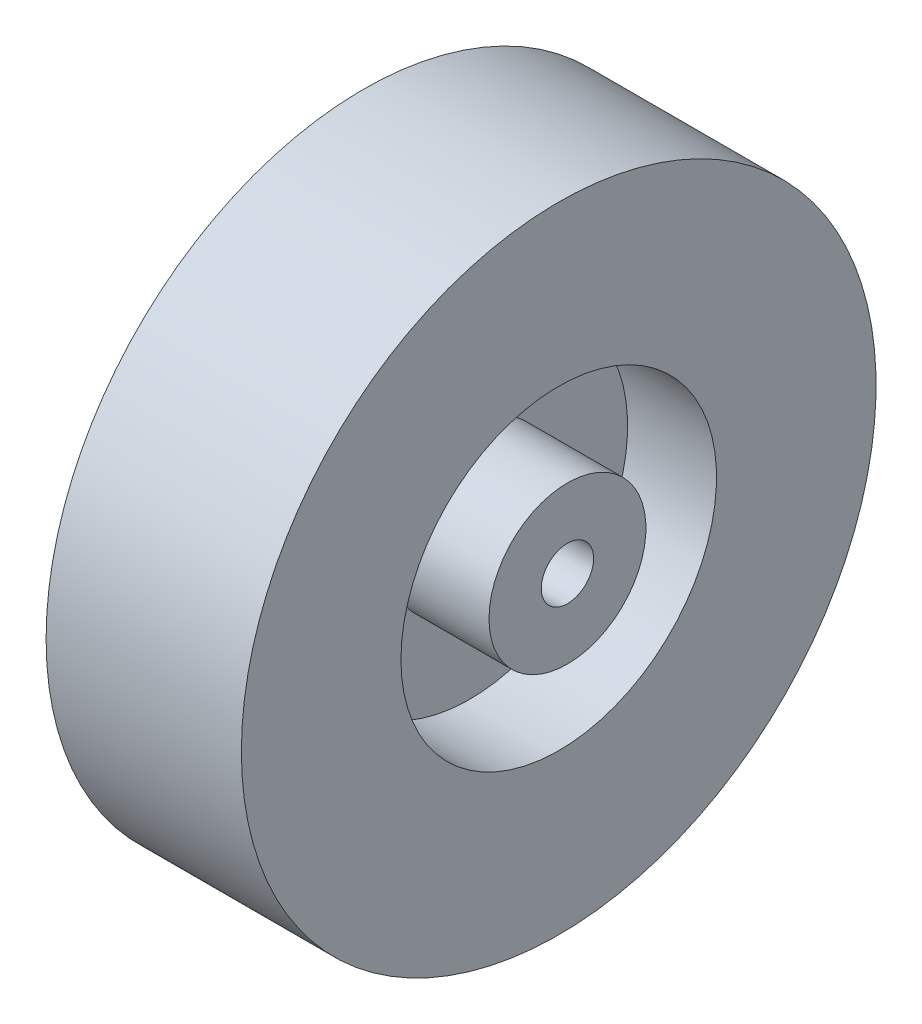
SolidWorks part; units mm, degrees
ref_plane "Front Plane" through (0, 0, 0) normal (0, 0, 1) x (1, 0, 0)
ref_plane "Top Plane" through (0, 0, 0) normal (0, 1, 0) x (1, 0, 0)
ref_plane "Right Plane" through (0, 0, 0) normal (1, 0, 0) x (0, 0, -1)
sketch "Sketch1" plane through (0, 0, 0) normal (0, 0, 1) x (1, 0, 0)
  line L0 (0, 36.4) -> (0, -12.6209) construction
  line L1 (-11.2, 18.1) -> (-1, 18.1)
  line L2 (11.2, 36.4) -> (-11.2, 36.4)
  line L3 (-11.2, 36.4) -> (-11.2, 18.1)
  line L4 (-13.5809, 0) -> (0, 0) construction
  line L5 (-1, 18.1) -> (-1, 9)
  line L6 (-1, 9) -> (-12.2, 9)
  line L7 (-12.2, 9) -> (-12.2, 0)
  line L8 (0, 0) -> (22.7343, 0) construction
  line L9 (12.2, 9) -> (12.2, 0)
  line L10 (1, 9) -> (12.2, 9)
  line L11 (1, 18.1) -> (1, 9)
  line L12 (11.2, 36.4) -> (11.2, 18.1)
  line L13 (11.2, 18.1) -> (1, 18.1)
  line L14 (-12.2, 0) -> (12.2, 0)
  dimension "D1" = 11.2
  dimension "D2" = 18.3
  dimension "D3" = 10.2
  dimension "D4" = 9
  dimension "D5" = 9.1
  dimension "D6" = 11.2
revolve "Revolve1" add sketch "Sketch1" angle 360 about L8
sketch "Sketch2" plane through (12.2, 0, 0) normal (1, 0, 0) x (0, 0, -1)
  circle A0 centre (0, 0) radius 3
  dimension "D1" = 6
extrude "Cut-Extrude1" cut sketch "Sketch2" against normal blind 15
scale "Echelle1" scale about centroid uniform scaling yes scale factor 0.5
